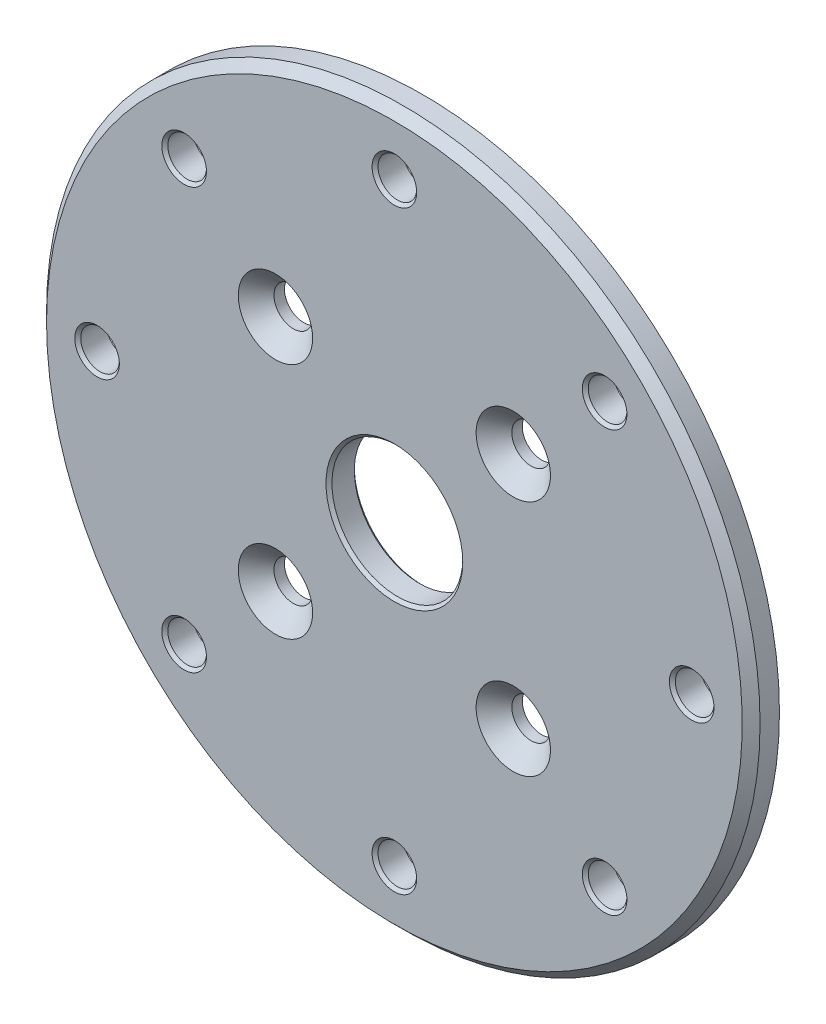
SolidWorks part; units mm, degrees
ref_plane "Alzado" through (0, 0, 0) normal (0, 0, 1) x (1, 0, 0)
ref_plane "Planta" through (0, 0, 0) normal (0, 1, 0) x (1, 0, 0)
ref_plane "Vista lateral" through (0, 0, 0) normal (1, 0, 0) x (0, 0, -1)
sketch "Croquis1" plane through (0, 0, 0) normal (0, 0, 1) x (1, 0, 0)
  circle A0 centre (0, 0) radius 60
  dimension "D1" = 120
extrude "Saliente-Extruir1" add sketch "Croquis1" along normal blind 4.7625
sketch "Croquis2" plane through (0, 0, 4.7625) normal (0, 0, 1) x (1, 0, 0)
  line L0 (0, 0) -> (60, 0) construction
  circle A0 centre (0, 0) radius 60 construction
  circle A1 centre (50, 0) radius 3.25
  circle A2 centre (35.3553, -35.3553) radius 3.25
  circle A3 centre (0, -50) radius 3.25
  circle A4 centre (-35.3553, -35.3553) radius 3.25
  circle A5 centre (-50, 0) radius 3.25
  circle A6 centre (-35.3553, 35.3553) radius 3.25
  circle A7 centre (0, 50) radius 3.25
  circle A8 centre (35.3553, 35.3553) radius 3.25
  point P24 (0, 0)
  dimension "D1" = 6.5
  dimension "D2" = 50
  dimension "D3" = 8
extrude "Cortar-Extruir1" cut sketch "Croquis2" against normal through all
chamfer "Chaflán1" distance 1.5 angle 45 1 edges at (60, 0, 4.7625)
sketch "Croquis3" plane through (0, 0, 4.7625) normal (0, 0, 1) x (1, 0, 0)
  circle A0 centre (0, 0) radius 11
  dimension "D1" = 22
extrude "Cortar-Extruir2" cut sketch "Croquis3" against normal through all
sketch "Croquis4" plane through (0, 0, 4.7625) normal (0, 0, 1) x (1, 0, 0)
  line L1 (-20, 20) -> (20, 20) construction
  line L2 (-20, 20) -> (-20, -20) construction
  line L3 (-20, -20) -> (20, -20) construction
  line L4 (20, 20) -> (20, -20) construction
  line L5 (-20, 20) -> (20, -20) construction
  line L6 (-20, -20) -> (20, 20) construction
  circle A1 centre (20, 20) radius 3.25
  circle A2 centre (-20, 20) radius 3.25
  circle A3 centre (-20, -20) radius 3.25
  circle A4 centre (20, -20) radius 3.25
  point P0 (0, 0)
  point P16 (0, 0)
  dimension "D1" = 40
  dimension "D2" = 40
  dimension "D3" = 6.5
  dimension "D4" = 6.5
  dimension "D5" = 6.5
  dimension "D6" = 6.5
extrude "Cortar-Extruir3" cut sketch "Croquis4" against normal through all
chamfer "Chaflán2" distance 0.5 angle 45 10 edges at (3.25, 50, 4.7625) (38.6053, 35.3553, 4.7625) (53.25, 0, 4.7625) (38.6053, -35.3553, 4.7625) (3.25, -50, 4.7625) (-32.1053, -35.3553, 4.7625) (-46.75, 0, 4.7625) (-32.1053, 35.3553, 4.7625) (11, 0, 0) (11, 0, 4.7625)
chamfer "Chaflán3" distance 3 angle 45 4 edges at (-16.75, -20, 4.7625) (23.25, -20, 4.7625) (23.25, 20, 4.7625) (-16.75, 20, 4.7625)
